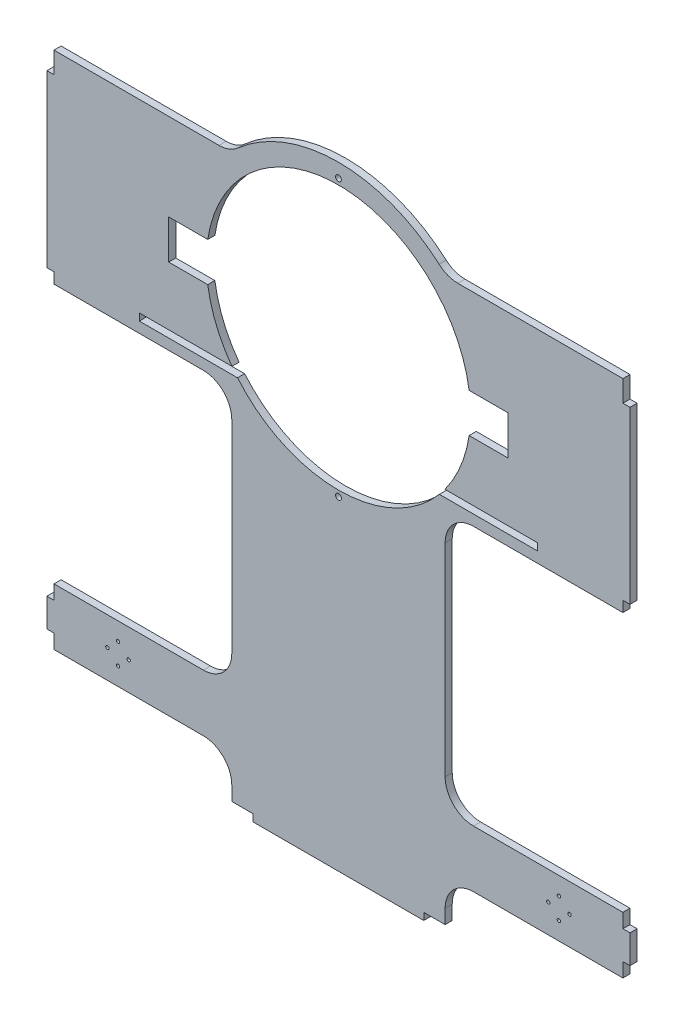
SolidWorks part; units mm, degrees
ref_plane "Front Plane" through (0, 0, 0) normal (0, 0, 1) x (1, 0, 0)
ref_plane "Top Plane" through (0, 0, 0) normal (0, 1, 0) x (1, 0, 0)
ref_plane "Right Plane" through (0, 0, 0) normal (1, 0, 0) x (0, 0, -1)
sketch "Main Body Sketch" plane through (0, 0, 0) normal (0, 0, 1) x (1, 0, 0)
  line L0 (-96.5459, -95.25) -> (-254, -95.25)
  line L1 (-254, 95.25) -> (-254, -95.25)
  line L2 (96.5459, 95.25) -> (254, 95.25)
  line L3 (254, 95.25) -> (254, -95.25)
  line L4 (254, -95.25) -> (96.5459, -95.25)
  line L5 (-96.5459, 95.25) -> (-254, 95.25)
  line L6 (-95.25, -96.5459) -> (-95.25, -406.4)
  line L7 (-95.25, -406.4) -> (95.25, -406.4)
  line L8 (95.25, -406.4) -> (95.25, -96.5459)
  circle A0 centre (0, 0) radius 117.9995
  arc A1 (-96.5459, -95.25) -> (-95.25, -96.5459) centre (0, 0) ccw
  arc A4 (96.5459, 95.25) -> (-96.5459, 95.25) centre (0, 0) ccw
  arc A5 (95.25, -96.5459) -> (96.5459, -95.25) centre (0, 0) ccw
  point P15 (0, -406.4)
  point P16 (254, 0)
  point P17 (-254, 0)
  dimension "D1" = 235.999
  dimension "D2" = 271.2466
  dimension "D3" = 95.25
  dimension "D4" = 254
  dimension "D7" = 406.4
  dimension "D11" = 190.5
extrude "Main Body" add sketch "Main Body Sketch" along normal mid plane 6.35
sketch "Tabs Sketch" plane through (0, 0, 3.175) normal (0, 0, 1) x (1, 0, 0)
  line L1 (-260.35, 76.2) -> (-254, 76.2)
  line L2 (-260.35, 76.2) -> (-260.35, -76.2)
  line L3 (-260.35, -76.2) -> (-254, -76.2)
  line L4 (-254, 76.2) -> (-254, -76.2)
  line L10 (-254, 95.25) -> (-254, -95.25) construction
  line L11 (-95.25, -406.4) -> (95.25, -406.4) construction
  line L12 (-76.2, -406.4) -> (76.2, -406.4)
  line L13 (-76.2, -406.4) -> (-76.2, -412.75)
  line L14 (-76.2, -412.75) -> (76.2, -412.75)
  line L15 (76.2, -406.4) -> (76.2, -412.75)
  point P6 (-260.35, 0)
  point P13 (0, -412.75)
  dimension "D1" = 6.35
  dimension "D2" = 6.35
  dimension "D3" = 152.4
  dimension "D4" = 152.4
extrude "Outside Tabs" add sketch "Tabs Sketch" against normal up to surface (6.35 mm away)
mirror "Outside Tabs Mirror" about plane through (0, 0, 0) normal (1, 0, 0) of "Outside Tabs"
hole_wizard "#6 (0.204) Tube Mount" positions "Sketch8" profile "Sketch9" hole size "#6" standard "ANSI Inch" end condition through all
sketch "Sketch8" plane through (0, 0, 3.175) normal (0, 0, 1) x (1, 0, 0)
  circle A0 centre (0, 0) radius 123.19
  point P5 (123.19, 0)
  point P7 (0, 123.19)
  point P9 (-123.19, 0)
  point P11 (0, -123.19)
  dimension "D1" = 246.38
sketch "Sketch9" plane through (0, -123.19, 3.175) normal (1, 0, 0) x (0, -1, 0)
  line L0 (0, 0) -> (0, 6.35)
  line L1 (0, 6.35) -> (2.5908, 6.35)
  line L2 (2.5908, 6.35) -> (2.5908, 0)
  line L5 (2.5908, 0) -> (0, 0)
  line L11 (0, -6.35) -> (0, 107.95) construction
  dimension "Thru Hole Dia." = 5.1816
  dimension "Thru Hole Depth" = 6.35
sketch "Thruster Cross Beams" plane through (0, 0, 3.175) normal (0, 0, 1) x (1, 0, 0)
  line L0 (-260.35, 76.2) -> (-260.35, -76.2) construction
  line L1 (-260.35, -57.15) -> (-203.2, -57.15)
  line L2 (-260.35, -57.15) -> (-260.35, -63.5)
  line L3 (-260.35, -63.5) -> (-203.2, -63.5)
  line L4 (-203.2, -57.15) -> (-203.2, -63.5)
  dimension "D2" = 57.15
  dimension "D3" = 6.35
  dimension "D4" = 57.15
extrude "Thruster Mounts" [suppressed] cut sketch "Thruster Cross Beams" against normal through all
mirror "Thruster Mirror" [suppressed] about plane through (0, 0, 0) normal (1, 0, 0)
sketch "Sketch11" plane through (0, 0, 3.175) normal (0, 0, 1) x (1, 0, 0)
  line L0 (-175.273, 53.95) -> (-184.773, 44.45)
  line L1 (-184.773, 44.45) -> (-175.273, 34.95)
  line L2 (-175.273, 34.95) -> (-165.773, 44.45)
  line L3 (-165.773, 44.45) -> (-175.273, 53.95)
  line L4 (-96.5459, 95.25) -> (-254, 95.25) construction
  circle A0 centre (-175.273, 53.95) radius 1.5
  circle A1 centre (-165.773, 44.45) radius 1.5
  circle A2 centre (-175.273, 34.95) radius 1.5
  circle A3 centre (-184.773, 44.45) radius 1.5
  point P11 (-175.273, 95.25)
  dimension "D2" = 3
  dimension "D1" = 19
  dimension "D3" = 50.8
extrude "Vertical Thruster Mounts" [suppressed] cut sketch "Sketch11" against normal through all contours A0 | A3 | A2 | A1
mirror "Mirror1" [suppressed] about plane through (0, 0, 0) normal (1, 0, 0)
sketch "Sketch12" plane through (0, 0, 3.175) normal (0, 0, 1) x (1, 0, 0)
  line L0 (-95.25, -96.5459) -> (-95.25, -406.4) construction
  line L1 (-95.25, -317.5) -> (-260.35, -317.5)
  line L2 (-95.25, -317.5) -> (-95.25, -368.3)
  line L3 (-95.25, -368.3) -> (-260.35, -368.3)
  line L4 (-260.35, -317.5) -> (-260.35, -368.3)
  line L6 (260.35, -317.5) -> (95.25, -317.5)
  line L7 (260.35, -317.5) -> (260.35, -368.3)
  line L8 (260.35, -368.3) -> (95.25, -368.3)
  line L9 (95.25, -317.5) -> (95.25, -368.3)
  line L10 (95.25, -406.4) -> (95.25, -96.5459) construction
  line L12 (-260.35, 76.2) -> (-260.35, -76.2) construction
  line L13 (260.35, 76.2) -> (260.35, -76.2) construction
  line M27 (95.25, -406.4) -> (95.25, -96.5459)
  line M45 (-95.25, -96.5459) -> (-95.25, -406.4)
  dimension "D1" = 50.8
  dimension "D2" = 38.1
extrude "Boss-Extrude1" add sketch "Sketch12" against normal up to surface (6.35 mm away) contours L1 L4 L3 M45 | L8 L7 L6 M27
sketch "Sketch13" plane through (0, 0, 3.175) normal (0, 0, 1) x (1, 0, 0)
  line L0 (-196.85, -333.4) -> (-206.35, -342.9)
  line L1 (-206.35, -342.9) -> (-196.85, -352.4)
  line L2 (-196.85, -352.4) -> (-187.35, -342.9)
  line L3 (-187.35, -342.9) -> (-196.85, -333.4)
  line L4 (-260.35, -317.5) -> (-260.35, -368.3) construction
  line L6 (-95.25, -368.3) -> (-260.35, -368.3) construction
  circle A0 centre (-196.85, -333.4) radius 1.5
  circle A1 centre (-187.35, -342.9) radius 1.5
  circle A2 centre (-196.85, -352.4) radius 1.5
  circle A3 centre (-206.35, -342.9) radius 1.5
  dimension "D2" = 3
  dimension "D1" = 19
  dimension "D3" = 63.5
  dimension "D4" = 25.4
extrude "Cut-Extrude1" cut sketch "Sketch13" against normal through all contours A0 | A1 | A2 | A3
mirror "Mirror2" about plane through (0, 0, 0) normal (1, 0, 0) of "Cut-Extrude1"
sketch "Sketch14" plane through (0, 0, 3.175) normal (0, 0, 1) x (1, 0, 0)
  line L1 (-260.35, -317.5) -> (-254, -317.5)
  line L2 (-260.35, -317.5) -> (-260.35, -330.2)
  line L3 (-260.35, -330.2) -> (-254, -330.2)
  line L4 (-254, -317.5) -> (-254, -330.2)
  line L5 (-260.35, -368.3) -> (-254, -368.3)
  line L6 (-260.35, -368.3) -> (-260.35, -355.6)
  line L7 (-260.35, -355.6) -> (-254, -355.6)
  line L8 (-254, -368.3) -> (-254, -355.6)
  dimension "D1" = 6.35
  dimension "D2" = 12.7
  dimension "D3" = 6.35
  dimension "D4" = 12.7
extrude "Cut-Extrude2" cut sketch "Sketch14" against normal through all
mirror "Mirror3" about plane through (0, 0, 0) normal (1, 0, 0) of "Cut-Extrude2"
sketch "Sketch15" plane through (0, 0, 3.175) normal (0, 0, 1) x (1, 0, 0)
  line L1 (-177.8, -69.85) -> (-90.0969, -69.85)
  line L2 (-177.8, -69.85) -> (-177.8, -76.2)
  line L3 (-177.8, -76.2) -> (-90.0969, -76.2)
  line L4 (-90.0969, -69.85) -> (-90.0969, -76.2)
  line L5 (-260.35, 76.2) -> (-260.35, -76.2) construction
  line L7 (177.8, -76.2) -> (90.0969, -76.2)
  line L8 (177.8, -76.2) -> (177.8, -69.85)
  line L9 (177.8, -69.85) -> (90.0969, -69.85)
  line L10 (90.0969, -76.2) -> (90.0969, -69.85)
  line L11 (-96.5459, -95.25) -> (-254, -95.25) construction
  circle A0 centre (0, 0) radius 117.9995 construction
  dimension "D1" = 6.35
  dimension "D2" = 19.05
  dimension "D3" = 82.55
extrude "Cut-Extrude3" cut sketch "Sketch15" against normal through all
sketch "Sketch16" plane through (0, 0, 3.175) normal (0, 0, 1) x (1, 0, 0)
  line L1 (116.7002, 17.4625) -> (151.6252, 17.4625)
  line L2 (116.7002, 17.4625) -> (116.7002, -17.4625)
  line L3 (116.7002, -17.4625) -> (151.6252, -17.4625)
  line L4 (151.6252, 17.4625) -> (151.6252, -17.4625)
  arc A0 (95.1045, -69.85) -> (-95.1045, -69.85) centre (0, 0) ccw construction
  dimension "D1" = 34.925
extrude "Cut-Extrude4" cut sketch "Sketch16" against normal through all
mirror "Mirror4" about plane through (0, 0, 0) normal (1, 0, 0) of "Cut-Extrude4"
sketch "Sketch17" plane through (0, 0, 3.175) normal (0, 0, 1) x (1, 0, 0)
  line L0 (-254, -76.2) -> (-254, -95.25) construction
  line L1 (-95.25, -96.5459) -> (-254, -96.5459)
  line L2 (-95.25, -96.5459) -> (-95.25, -85.725)
  line L3 (-95.25, -85.725) -> (-254, -85.725)
  line L4 (-254, -96.5459) -> (-254, -85.725)
extrude "Cut-Extrude5" cut sketch "Sketch17" against normal through all
mirror "Mirror5" about plane through (0, 0, 0) normal (1, 0, 0) of "Cut-Extrude5"
fillet "Fillet1" radius 25.4 8 edges at (95.25, -85.725, 0) (-95.25, -85.725, 0) (96.5459, 95.25, 0) (-96.5459, 95.25, 0) (-95.25, -317.5, 0) (95.25, -317.5, 0) (95.25, -368.3, 0) (-95.25, -368.3, 0)
